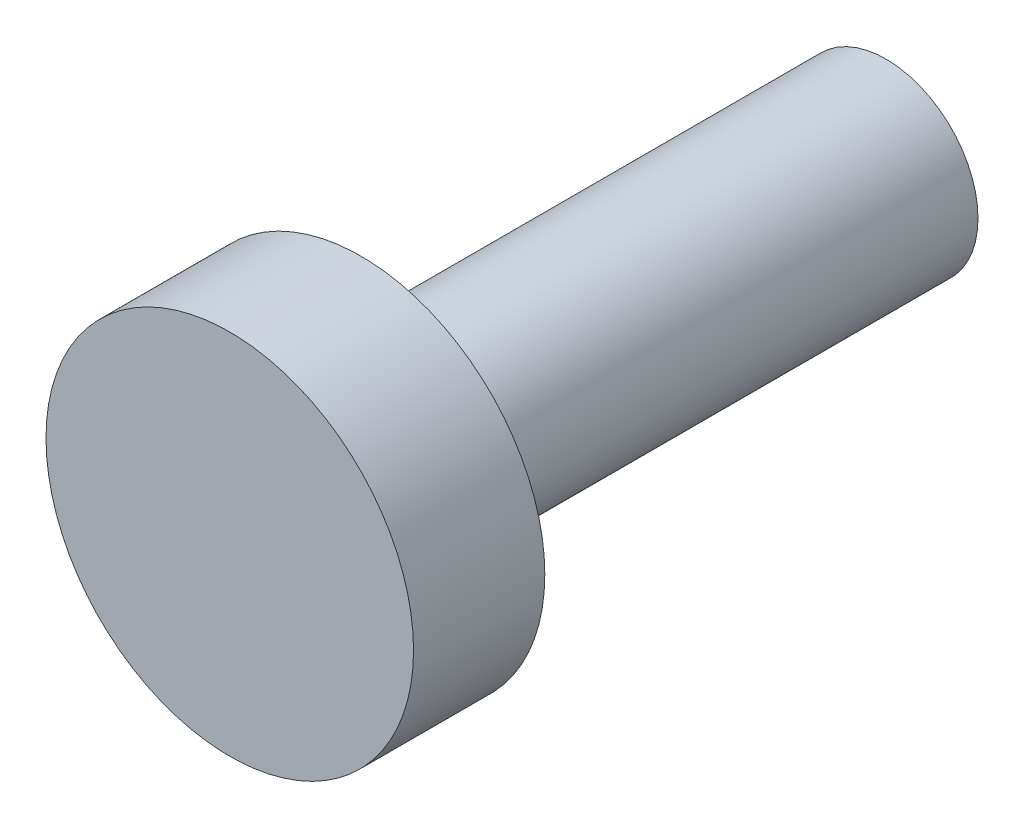
SolidWorks part; units mm, degrees
ref_plane "Front" through (0, 0, 0) normal (0, 0, 1) x (1, 0, 0)
ref_plane "Top" through (0, 0, 0) normal (0, 1, 0) x (1, 0, 0)
ref_plane "Right" through (0, 0, 0) normal (1, 0, 0) x (0, 0, -1)
sketch "Sketch1" plane through (0, 0, 0) normal (0, 0, 1) x (1, 0, 0)
  circle A0 centre (0, 0) radius 1.75
  dimension "D1" = 3.5
extrude "Boss-Extrude1" add sketch "Sketch1" along normal blind 10
sketch "Sketch2" plane through (0, 0, 10) normal (0, 0, 1) x (1, 0, 0)
  circle A0 centre (0, 0) radius 3.5
  dimension "D1" = 7
extrude "Boss-Extrude2" add sketch "Sketch2" along normal blind 2.5
